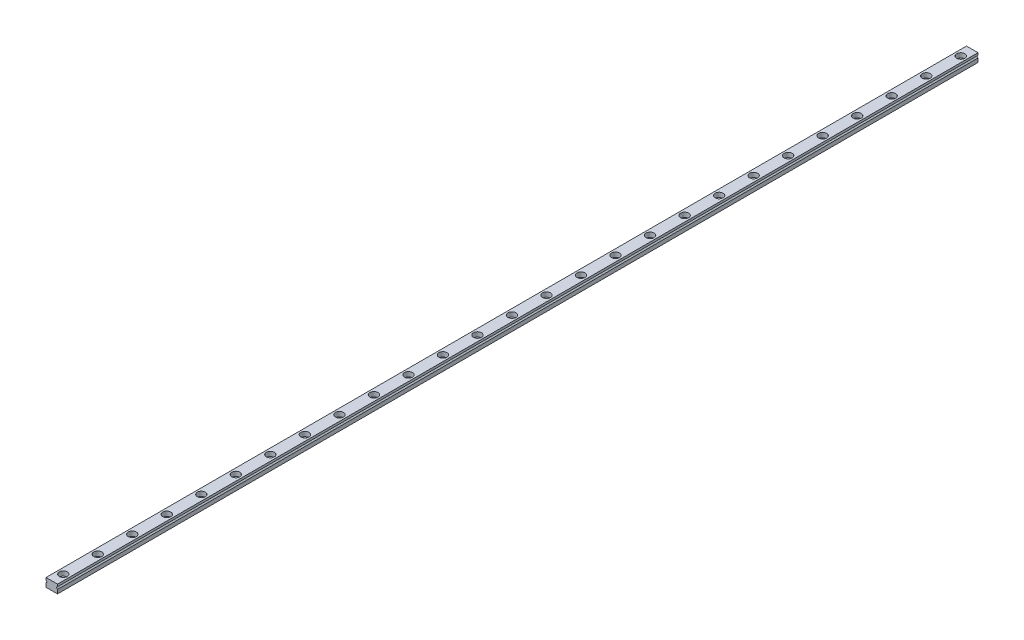
SolidWorks part; units mm, degrees
material "AISI 304"
ref_plane "前视基准面" through (0, 0, 0) normal (0, 0, 1) x (1, 0, 0)
ref_plane "上视基准面" through (0, 0, 0) normal (0, 1, 0) x (1, 0, 0)
ref_plane "右视基准面" through (0, 0, 0) normal (1, 0, 0) x (0, 0, -1)
sketch "Sketch1" plane through (0, 0, 0) normal (0, 0, 1) x (1, 0, 0)
  line L0 (0, 0) -> (0, 3.7)
  line L1 (0, 3.7) -> (5, 3.7)
  line L2 (5, 3.7) -> (5, 0)
  line L3 (5, 0) -> (0, 0)
  dimension "D1" = 3.7
  dimension "D2" = 5
extrude "Boss-Extrude1" add sketch "Sketch1" against normal blind 400
sketch "Sketch2" plane through (0, 3.7, 0) normal (0, 1, 0) x (1, 0, 0)
  line L0 (2.5, -0.9977) -> (2.5, 11.7262) construction
  line L1 (-6.0403, 5) -> (12.1202, 5) construction
  line L2 (5, 0) -> (0, 0) construction
  line L3 (5, 400) -> (5, 0) construction
  circle A0 centre (2.5, 5) radius 1.75
  circle A1 centre (2.5, 20) radius 1.75
  circle A2 centre (2.5, 35) radius 1.75
  circle A3 centre (2.5, 50) radius 1.75
  circle A4 centre (2.5, 65) radius 1.75
  circle A5 centre (2.5, 80) radius 1.75
  circle A6 centre (2.5, 95) radius 1.75
  circle A7 centre (2.5, 110) radius 1.75
  circle A8 centre (2.5, 125) radius 1.75
  circle A9 centre (2.5, 140) radius 1.75
  circle A10 centre (2.5, 155) radius 1.75
  circle A11 centre (2.5, 170) radius 1.75
  circle A12 centre (2.5, 185) radius 1.75
  circle A13 centre (2.5, 200) radius 1.75
  circle A14 centre (2.5, 215) radius 1.75
  circle A15 centre (2.5, 230) radius 1.75
  circle A16 centre (2.5, 245) radius 1.75
  circle A17 centre (2.5, 260) radius 1.75
  circle A18 centre (2.5, 275) radius 1.75
  circle A19 centre (2.5, 290) radius 1.75
  circle A20 centre (2.5, 305) radius 1.75
  circle A21 centre (2.5, 320) radius 1.75
  circle A22 centre (2.5, 335) radius 1.75
  circle A23 centre (2.5, 350) radius 1.75
  circle A24 centre (2.5, 365) radius 1.75
  circle A25 centre (2.5, 380) radius 1.75
  circle A26 centre (2.5, 395) radius 1.75
  dimension "D3" = 3.5
  dimension "D1" = 5
  dimension "D2" = 2.5
  dimension "D5" = 390
  dimension "D4" = 27
extrude "Cut-Extrude1" cut sketch "Sketch2" against normal blind 2
sketch "Sketch3" plane through (0, 1.7, 0) normal (0, 1, 0) x (1, 0, 0)
  circle A0 centre (2.5, 5) radius 1
  circle A1 centre (2.5, 20) radius 1
  circle A2 centre (2.5, 35) radius 1
  circle A3 centre (2.5, 50) radius 1
  circle A4 centre (2.5, 65) radius 1
  circle A5 centre (2.5, 80) radius 1
  circle A6 centre (2.5, 95) radius 1
  circle A7 centre (2.5, 110) radius 1
  circle A8 centre (2.5, 125) radius 1
  circle A9 centre (2.5, 140) radius 1
  circle A10 centre (2.5, 155) radius 1
  circle A11 centre (2.5, 170) radius 1
  circle A12 centre (2.5, 185) radius 1
  circle A13 centre (2.5, 200) radius 1
  circle A14 centre (2.5, 215) radius 1
  circle A15 centre (2.5, 230) radius 1
  circle A16 centre (2.5, 245) radius 1
  circle A17 centre (2.5, 260) radius 1
  circle A18 centre (2.5, 275) radius 1
  circle A19 centre (2.5, 290) radius 1
  circle A20 centre (2.5, 305) radius 1
  circle A21 centre (2.5, 320) radius 1
  circle A22 centre (2.5, 335) radius 1
  circle A23 centre (2.5, 350) radius 1
  circle A24 centre (2.5, 365) radius 1
  circle A25 centre (2.5, 380) radius 1
  circle A26 centre (2.5, 395) radius 1
  dimension "D1" = 2
  dimension "D3" = 390
  dimension "D2" = 27
extrude "Cut-Extrude2" cut sketch "Sketch3" against normal through all
sketch "Sketch4" plane through (0, 0, 0) normal (0, 0, 1) x (1, 0, 0)
  line L0 (2.5, 3.8064) -> (2.5, -0.1865) construction
  line L1 (5, 0) -> (5, 3.7) construction
  line L2 (0, 2.7) -> (0.5, 2.2)
  line L3 (0, 3.7) -> (0, 0) construction
  line L4 (0.5, 2.2) -> (0, 1.7)
  line L5 (0, 2.7) -> (0, 1.7)
  line L6 (5, 2.7) -> (4.5, 2.2)
  line L7 (4.5, 2.2) -> (5, 1.7)
  line L8 (5, 2.7) -> (5, 1.7)
  dimension "D1" = 2.5
  dimension "D2" = 45
  dimension "D3" = 45
  dimension "D4" = 1
  dimension "D5" = 0.5
extrude "Cut-Extrude3" cut sketch "Sketch4" against normal through all
